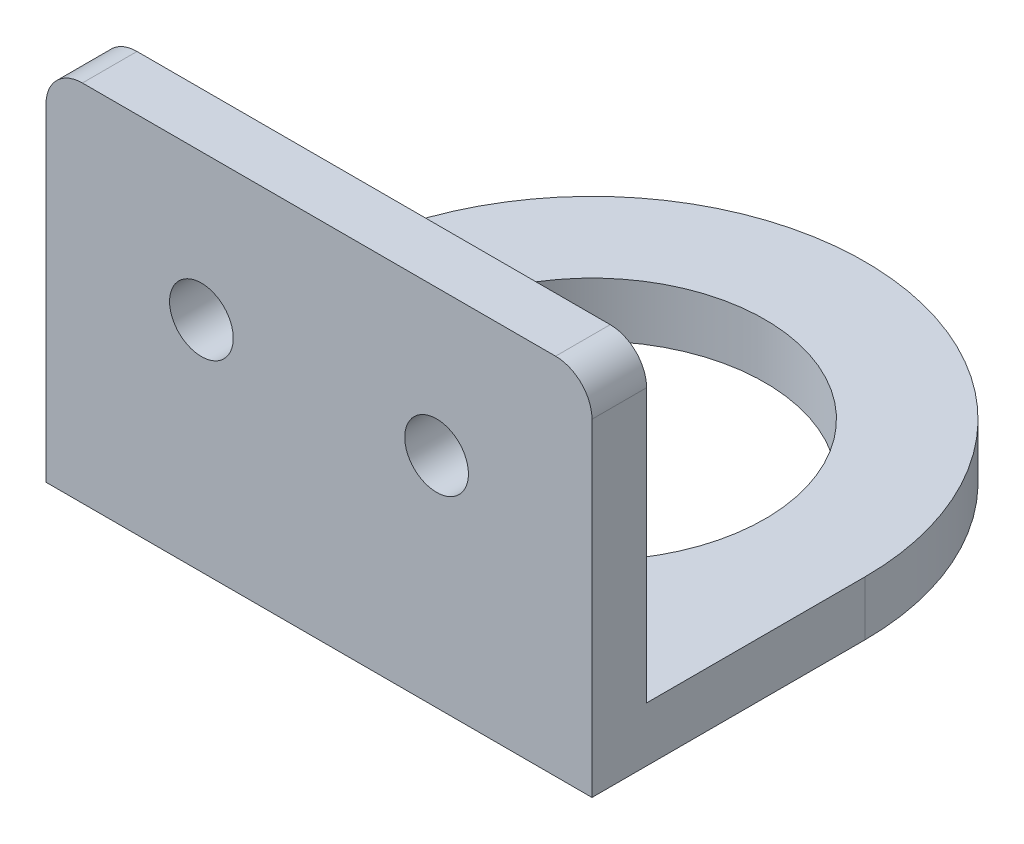
SolidWorks part; units mm, degrees
ref_plane "前视基准面" through (0, 0, 0) normal (0, 0, 1) x (1, 0, 0)
ref_plane "上视基准面" through (0, 0, 0) normal (0, 1, 0) x (1, 0, 0)
ref_plane "右视基准面" through (0, 0, 0) normal (1, 0, 0) x (0, 0, -1)
sketch "草图1" plane through (0, 0, 0) normal (0, 1, 0) x (1, 0, 0)
  line L0 (15, 0) -> (15, -50)
  line L1 (-15, 0) -> (-15, -50)
  line L2 (-15, -50) -> (15, -50)
  line L3 (-15, -15) -> (15, -15)
  arc A0 (15, 0) -> (-15, 0) centre (0, 0) ccw
  circle A1 centre (0, 0) radius 9.5
  dimension "D1" = 50
  dimension "D2" = 15
  dimension "D3" = 35
extrude "凸台-拉伸2" add sketch "草图1" along normal blind 3 contours L0 A0 L1 L3 A1
sketch "草图9" plane through (0, 0, 15) normal (0, 0, 1) x (1, 0, 0)
  line L1 (-15, 0) -> (15, 0)
  line L2 (-15, 0) -> (-15, 20)
  line L3 (-15, 20) -> (15, 20)
  line L4 (15, 0) -> (15, 20)
  dimension "D1" = 20
extrude "凸台-拉伸3" add sketch "草图9" against normal blind 3
sketch "草图10" plane through (0, 0, 12) normal (0, 0, -1) x (-1, 0, 0)
  line L0 (-15, 20) -> (15, 20) construction
  line L1 (0, 33.0654) -> (0, -1.9614) construction
  circle A2 centre (6.4614, 12) radius 1.75
  circle A3 centre (-6.4614, 12) radius 1.75
  point P0 (-6.4614, 10.8637)
  point P15 (-24.8305, 15.8751)
  dimension "D1" = 8
extrude "切除-拉伸1" cut sketch "草图10" against normal through all
fillet "圆角6" radius 2 2 edges at (15, 20, 13.5) (-15, 20, 13.5)
